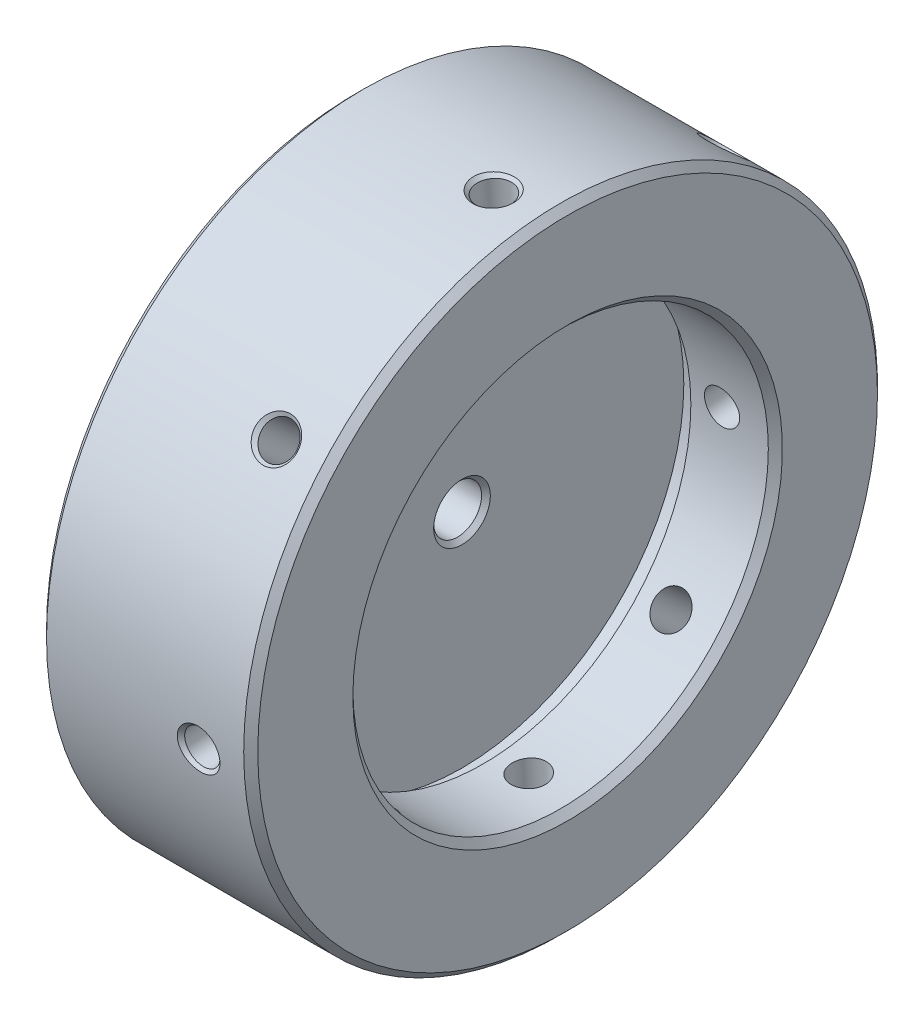
SolidWorks part; units mm, degrees
material "Сталь 40Х ГОСТ 4543-71"
ref_plane "Спереди (Плоскость XY)" through (0, 0, 0) normal (0, 0, 1) x (1, 0, 0)
ref_plane "Сверху (Плоскость XZ)" through (0, 0, 0) normal (0, 1, 0) x (1, 0, 0)
ref_plane "Справа (Плоскость ZY)" through (0, 0, 0) normal (1, 0, 0) x (0, 0, -1)
other "Configuration Table"
sketch "Эскиз1" plane through (0, 0, 0) normal (0, 0, 1) x (1, 0, 0)
  line L0 (0, 0) -> (60, 0) construction
  line L1 (0, 6.5) -> (11.2583, 0)
  line L2 (11.2583, 0) -> (30, 0)
  line L3 (30, 0) -> (30, 31.5)
  line L4 (33, 29.5) -> (45, 29.5)
  line L5 (45, 29.5) -> (45, 45)
  line L6 (45, 45) -> (15, 45)
  line L7 (15, 45) -> (15, 22.5)
  line L8 (15, 22.5) -> (0, 22.5)
  line L9 (0, 22.5) -> (0, 6.5)
  line L11 (30, 31.5) -> (33, 31.5)
  line L12 (33, 31.5) -> (33, 29.5)
  dimension "D1" = 13
  dimension "D2" = 30
  dimension "D3" = 59
  dimension "D4" = 15
  dimension "D5" = 90
  dimension "D6" = 45
  dimension "D7" = 15
  dimension "D8" = 15
  dimension "D9" = 2
  dimension "D10" = 3
revolve "Повернуть1" add sketch "Эскиз1" angle 360 about L0
chamfer "Фаска1" distance 1 angle 45 4 edges at (45, 0, 29.5) (45, 0, 45) (15, 0, 45) (0, 0, 22.5)
hole_wizard "Отверстие обработанное метчиком M81" positions "Эскиз4" profile "Эскиз3" tap size "M8" standard "DIN" end condition through all
sketch "Эскиз4" plane through (30, 0, 0) normal (1, 0, 0) x (0, 0, -1)
  point P0 (0, 0)
sketch "Эскиз3" plane through (30, 0, 0) normal (0, 1, 0) x (0, 0, -1)
  line L0 (0, 0) -> (0, 30)
  line L1 (0, 30) -> (3.4, 30)
  line L2 (3.4, 30) -> (3.4, 0.625)
  line L3 (3.4, 0.625) -> (4.025, 0)
  line L5 (4.025, 0) -> (0, 0)
  line L6 (-3.4, 0.625) -> (-4.025, 0) construction
  line L11 (0, -6.35) -> (0, 107.95) construction
  dimension "Диаметр проходного сверла" = 6.8
  dimension "Глубина проходного сверла" = 30
  dimension "Диаметр передней зенковки" = 8.05
  dimension "Угол передней зенковки" = 90
cosmetic thread "Отверстие резьбы1" parameters "D2"=8
hole_wizard "Отверстие обработанное метчиком M61" positions "Трехмерный эскиз1" profile "Эскиз5" tap size "M6" standard "DIN" end condition through all
sketch3d "Трехмерный эскиз1"
  point P0 (37.5, -3.0032, 44.8997)
  dimension "D1" = 7.5
sketch "Эскиз5" plane through (37.5, -3.0032, 44.8997) normal (1, 0, 0) x (0, -0.9978, -0.0667)
  line L0 (0, 0) -> (0, 92.9028)
  line L1 (0, 92.9028) -> (2.5, 92.9028)
  line L2 (2.5, 92.9028) -> (2.5, 0.525)
  line L3 (2.5, 0.525) -> (3.025, 0)
  line L5 (3.025, 0) -> (0, 0)
  line L6 (-2.5, 0.525) -> (-3.025, 0) construction
  line L11 (0, -6.35) -> (0, 107.95) construction
  dimension "Диаметр проходного сверла" = 5
  dimension "Глубина проходного сверла" = 92.9028
  dimension "Диаметр передней зенковки" = 6.05
  dimension "Угол передней зенковки" = 90
cosmetic thread "Отверстие резьбы2" parameters "D2"=6
pattern_circular "Круговой массив1" count 4 every 45 about axis through (0, 0, 0) along (-1, 0, 0) of "Отверстие обработанное метчиком M61"
